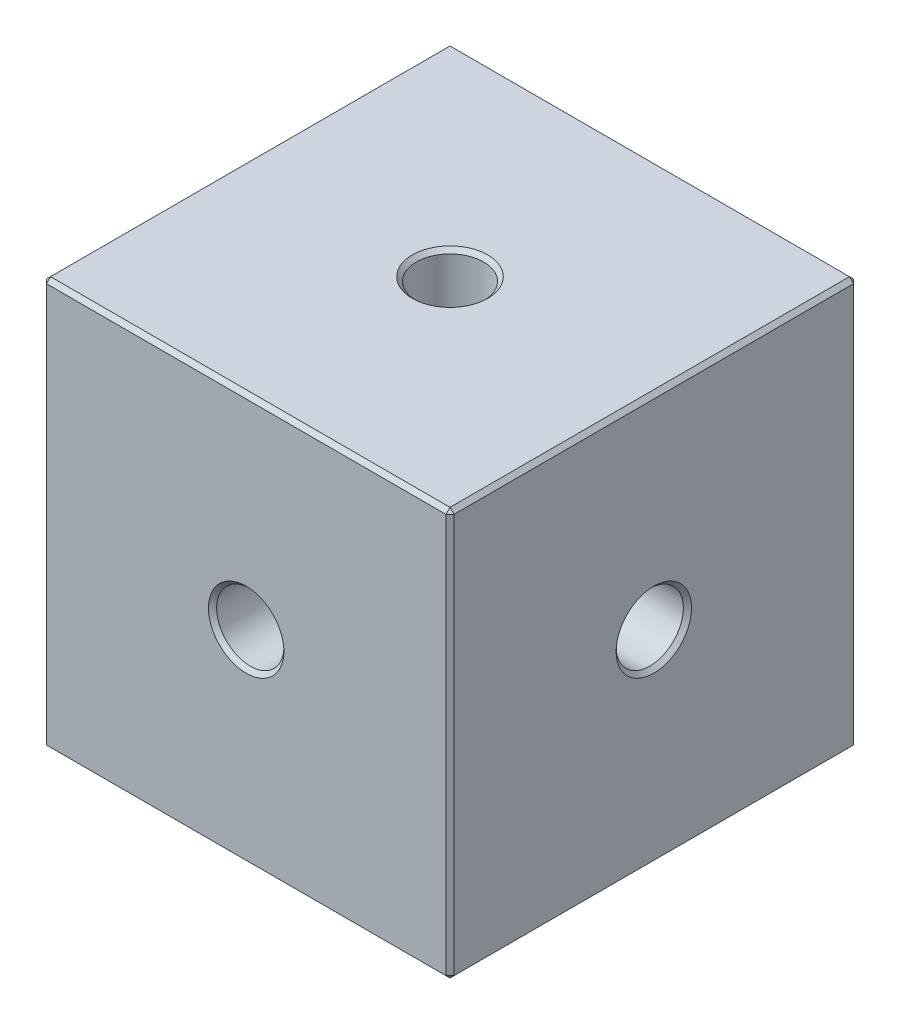
SolidWorks part; units mm, degrees
ref_plane "前视基准面" through (0, 0, 0) normal (0, 0, 1) x (1, 0, 0)
ref_plane "上视基准面" through (0, 0, 0) normal (0, 1, 0) x (1, 0, 0)
ref_plane "右视基准面" through (0, 0, 0) normal (1, 0, 0) x (0, 0, -1)
sketch "草图1" plane through (0, 0, 0) normal (0, 1, 0) x (1, 0, 0)
  line L1 (-10, 10) -> (10, 10)
  line L2 (-10, 10) -> (-10, -10)
  line L3 (-10, -10) -> (10, -10)
  line L4 (10, 10) -> (10, -10)
  line L5 (-10, 10) -> (10, -10) construction
  line L6 (-10, -10) -> (10, 10) construction
  point P0 (0, 0)
  dimension "D1" = 20
extrude "凸台-拉伸1" add sketch "草图1" along normal mid plane 20
hole_wizard "M4 螺纹孔1" positions "草图2" profile "草图3" tap size "M4" standard "GB" end condition through all
sketch "草图2" plane through (0, 0, 10) normal (0, 0, 1) x (1, 0, 0)
  point P0 (0, 0)
sketch "草图3" plane through (0, 0, 10) normal (1, 0, 0) x (0, -1, 0)
  line L0 (0, 0) -> (0, 20)
  line L1 (0, 20) -> (1.65, 20)
  line L2 (1.65, 20) -> (1.65, 0)
  line L5 (1.65, 0) -> (0, 0)
  line L11 (0, -6.35) -> (0, 107.95) construction
  dimension "通孔螺纹孔钻头直径" = 3.3
  dimension "通孔螺纹孔钻头深度" = 20
cosmetic thread "孔螺蚊线1" parameters "D2"=4
hole_wizard "M4 螺纹孔2" positions "草图4" profile "草图5" tap size "M4" standard "GB" end condition through all
sketch "草图4" plane through (0, 10, 0) normal (0, 1, 0) x (1, 0, 0)
  point P0 (0, 0)
sketch "草图5" plane through (0, 10, 0) normal (1, 0, 0) x (0, 0, 1)
  line L0 (0, 0) -> (0, 20)
  line L1 (0, 20) -> (1.65, 20)
  line L2 (1.65, 20) -> (1.65, 0)
  line L5 (1.65, 0) -> (0, 0)
  line L11 (0, -6.35) -> (0, 107.95) construction
  dimension "通孔螺纹孔钻头直径" = 3.3
  dimension "通孔螺纹孔钻头深度" = 20
cosmetic thread "孔螺蚊线2" parameters "D2"=4
hole_wizard "M4 螺纹孔3" positions "草图6" profile "草图7" tap size "M4" standard "GB" end condition through all
sketch "草图6" plane through (10, 0, 0) normal (1, 0, 0) x (0, 0, -1)
  point P0 (0, 0)
sketch "草图7" plane through (10, 0, 0) normal (0, 1, 0) x (0, 0, -1)
  line L0 (0, 0) -> (0, 20)
  line L1 (0, 20) -> (1.65, 20)
  line L2 (1.65, 20) -> (1.65, 0)
  line L5 (1.65, 0) -> (0, 0)
  line L11 (0, -6.35) -> (0, 107.95) construction
  dimension "通孔螺纹孔钻头直径" = 3.3
  dimension "通孔螺纹孔钻头深度" = 20
cosmetic thread "孔螺蚊线3" parameters "D2"=4
chamfer "倒角1" distance 0.2 angle 45 18 edges at (0, -10, 1.65) (-10, 0, -1.65) (1.65, 0, -10) (10, 0, -1.65) (1.65, 0, 10) (-10, -10, 0) (-10, 0, -10) (0, -10, -10) (10, 0, -10) (10, -10, 0) (-10, 0, 10) (0, -10, 10) (10, 0, 10) (0, 10, 10) (-10, 10, 0) (0, 10, -10) (10, 10, 0) (0, 10, 1.65)
